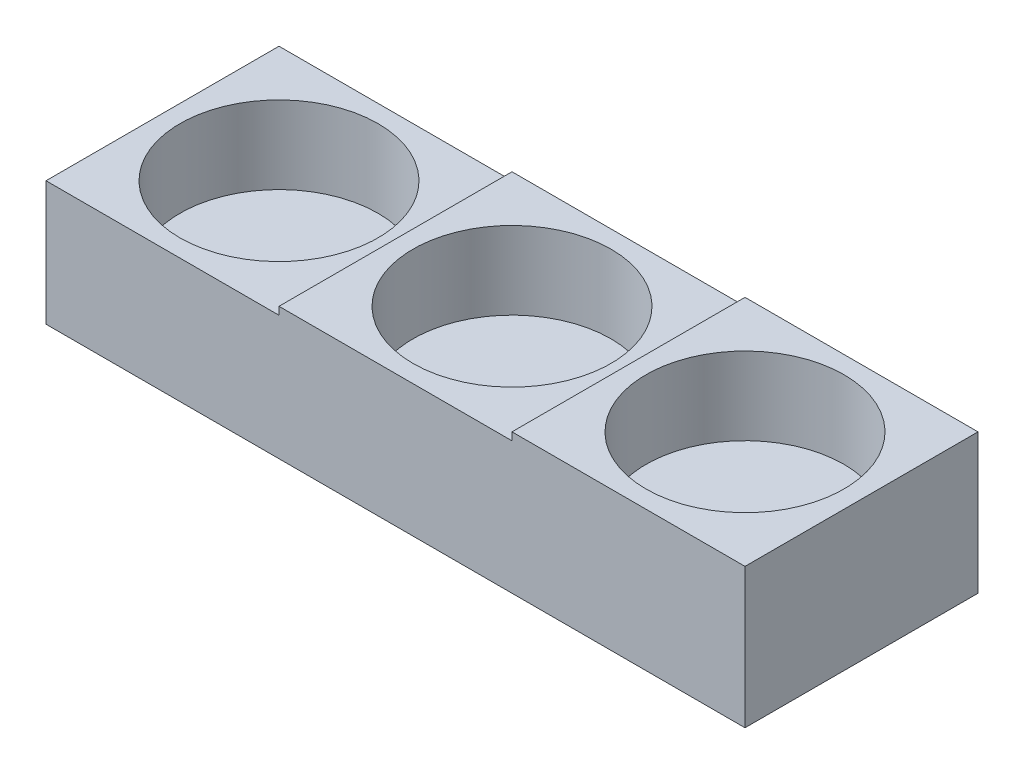
SolidWorks part; units mm, degrees
ref_plane "Front Plane" through (0, 0, 0) normal (0, 0, 1) x (1, 0, 0)
ref_plane "Top Plane" through (0, 0, 0) normal (0, 1, 0) x (1, 0, 0)
ref_plane "Right Plane" through (0, 0, 0) normal (1, 0, 0) x (0, 0, -1)
sketch "Sketch1" plane through (0, 0, 0) normal (0, 1, 0) x (1, 0, 0)
  line L0 (-45, 0) -> (45, 0) construction
  line L1 (45, -15) -> (-45, -15)
  line L2 (45, -15) -> (45, 15)
  line L3 (45, 15) -> (-45, 15)
  line L4 (-45, -15) -> (-45, 15)
  line L5 (45, -15) -> (-45, 15) construction
  line L6 (45, 15) -> (-45, -15) construction
  circle A0 centre (-30, 0) radius 9
  circle A1 centre (0, 0) radius 9
  circle A2 centre (30, 0) radius 9
  point P0 (0, 0)
  dimension "D1" = 18
  dimension "D2" = 30
  dimension "D3" = 30
  dimension "D4" = 30
  dimension "D5" = 90
extrude "Boss-Extrude1" add sketch "Sketch1" along normal blind 5
sketch "Sketch2" plane through (0, 5, 0) normal (0, 1, 0) x (1, 0, 0)
  line L0 (-45, -15) -> (45, -15) construction
  line L1 (-45, 15) -> (-15, 15)
  line L2 (-45, 15) -> (-45, -15)
  line L3 (-45, -15) -> (-15, -15)
  line L4 (-15, 15) -> (-15, -15)
  line L5 (-30, 0) -> (0, 0) construction
  point P11 (-15, 0)
extrude "Boss-Extrude2" add sketch "Sketch2" along normal blind 1
sketch "Sketch3" plane through (0, 5, 0) normal (0, 1, 0) x (1, 0, 0)
  line L1 (15, -15) -> (-15, -15)
  line L2 (15, -15) -> (15, 15)
  line L3 (15, 15) -> (-15, 15)
  line L4 (-15, -15) -> (-15, 15)
  line L5 (15, -15) -> (-15, 15) construction
  line L6 (15, 15) -> (-15, -15) construction
  point P0 (0, 0)
extrude "Boss-Extrude3" add sketch "Sketch3" along normal blind 2
sketch "Sketch4" plane through (0, 5, 0) normal (0, 1, 0) x (1, 0, 0)
  line L1 (15, -15) -> (45, -15)
  line L2 (15, -15) -> (15, 15)
  line L3 (15, 15) -> (45, 15)
  line L4 (45, -15) -> (45, 15)
extrude "Boss-Extrude4" add sketch "Sketch4" along normal blind 3
sketch "Sketch5" plane through (0, 6, 0) normal (0, 1, 0) x (1, 0, 0)
  line L1 (-15, 15) -> (-45, 15)
  line L2 (-15, 15) -> (-15, -15)
  line L3 (-15, -15) -> (-45, -15)
  line L4 (-45, 15) -> (-45, -15)
  circle A0 centre (-30, 0) radius 9 construction
  circle A1 centre (-30, 0) radius 9 construction
  circle A2 centre (-30, 0) radius 12.75
  dimension "D1" = 25.5
extrude "Boss-Extrude5" add sketch "Sketch5" along normal blind 10
sketch "Sketch6" plane through (0, 7, 0) normal (0, 1, 0) x (1, 0, 0)
  line L1 (15, -15) -> (-15, -15)
  line L2 (15, -15) -> (15, 15)
  line L3 (15, 15) -> (-15, 15)
  line L4 (-15, -15) -> (-15, 15)
  line L5 (15, -15) -> (-15, 15) construction
  line L6 (15, 15) -> (-15, -15) construction
  circle A0 centre (0, 0) radius 9 construction
  circle A1 centre (0, 0) radius 9 construction
  circle A2 centre (0, 0) radius 12.75
  dimension "D1" = 25.5
extrude "Boss-Extrude6" add sketch "Sketch6" along normal blind 10
sketch "Sketch7" plane through (0, 8, 0) normal (0, 1, 0) x (1, 0, 0)
  line L1 (15, -15) -> (45, -15)
  line L2 (15, -15) -> (15, 15)
  line L3 (15, 15) -> (45, 15)
  line L4 (45, -15) -> (45, 15)
  circle A0 centre (30, 0) radius 9 construction
  circle A1 centre (30, 0) radius 9
  circle A2 centre (30, 0) radius 12.75
  line M1 (15, 15) -> (15, -15)
  line M2 (15, -15) -> (45, -15)
  line M3 (45, -15) -> (45, 15)
  line M4 (45, 15) -> (15, 15)
  dimension "D1" = 25.5
extrude "Boss-Extrude7" add sketch "Sketch7" along normal blind 10 contours A2 M4 M1 M2 M3
equation "\"D4@Sketch1\"=\"D3@Sketch1\""
